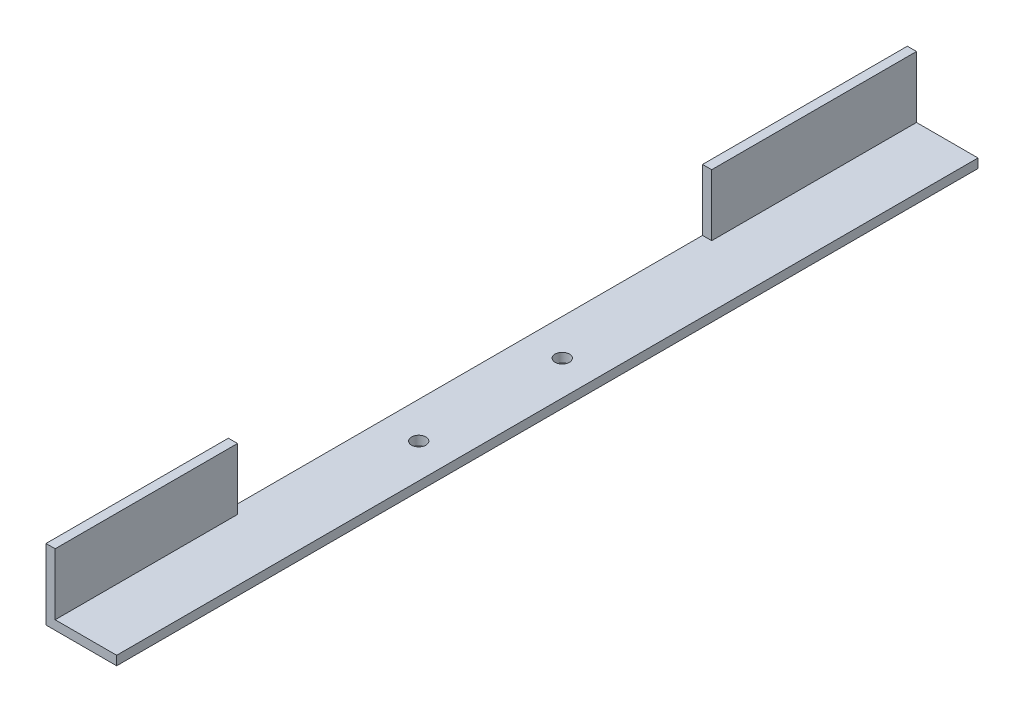
SolidWorks part; units mm, degrees
ref_plane "Front" through (0, 0, 0) normal (0, 0, 1) x (1, 0, 0)
ref_plane "Top" through (0, 0, 0) normal (0, 1, 0) x (1, 0, 0)
ref_plane "Right" through (0, 0, 0) normal (1, 0, 0) x (0, 0, -1)
sketch "草图1" plane through (0, 0, 0) normal (0, 0, 1) x (1, 0, 0)
  line L0 (0, 0) -> (0, 25)
  line L1 (0, 25) -> (3.24, 25)
  line L2 (3.24, 25) -> (3.24, 3.24)
  line L3 (3.24, 3.24) -> (25, 3.24)
  line L4 (0, 0) -> (25, 0)
  line L5 (25, 0) -> (25, 3.24)
  dimension "D1" = 3.24
  dimension "D2" = 3.24
  dimension "D3" = 25
  dimension "D4" = 25
extrude "凸台-拉伸1" add sketch "草图1" along normal blind 304.8
sketch "草图2" plane through (3.24, 0, 0) normal (1, 0, 0) x (0, 0, -1)
  line L0 (-304.8, 3.24) -> (0, 3.24) construction
  line L1 (-240.2735, 3.24) -> (-72.4717, 3.24)
  line L2 (-240.2735, 3.24) -> (-240.2735, 25)
  line L3 (-240.2735, 25) -> (-72.4717, 25)
  line L4 (-72.4717, 3.24) -> (-72.4717, 25)
  line L5 (-304.8, 25) -> (0, 25) construction
extrude "切除-拉伸1" cut sketch "草图2" against normal blind 304.8
sketch "草图4" plane through (0, 3.24, 0) normal (0, 1, 0) x (1, 0, 0)
  circle A0 centre (12.7975, -134.9151) radius 2.54
  circle A1 centre (12.8034, -185.7151) radius 2.54
  point P4 (12.8808, -132.039)
  point P5 (0, 0)
  point P6 (0, 0)
  point P7 (0, 0)
  point P8 (12.7975, -185.7151)
  dimension "D1" = 5.08
  dimension "D2" = 5.08
  dimension "D3" = 50.8
extrude "切除-拉伸2" cut sketch "草图4" against normal blind 304.8
